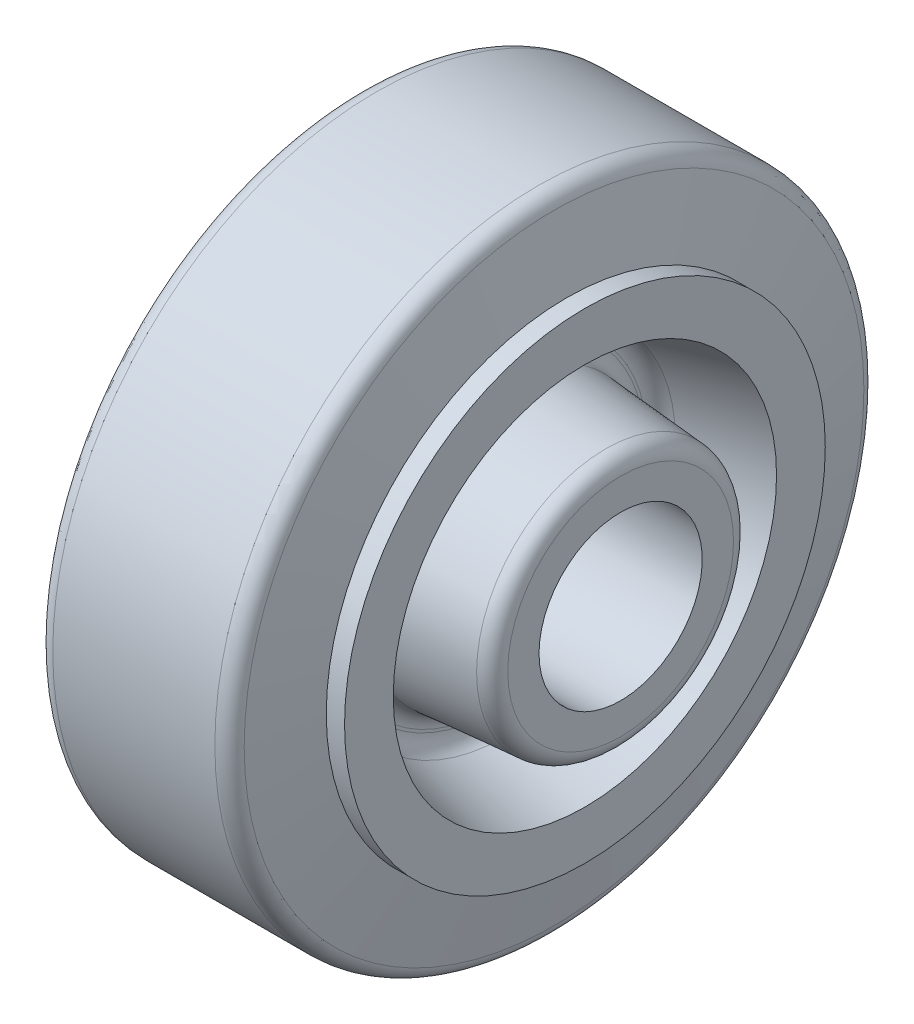
SolidWorks part; units mm, degrees
ref_plane "Front Plane" through (0, 0, 0) normal (0, 0, 1) x (1, 0, 0)
ref_plane "Top Plane" through (0, 0, 0) normal (0, 1, 0) x (1, 0, 0)
ref_plane "Right Plane" through (0, 0, 0) normal (1, 0, 0) x (0, 0, -1)
sketch "Sketch1" plane through (0, 0, 0) normal (0, 0, 1) x (1, 0, 0)
  line L0 (-11.65, -39.8) -> (11.65, -39.8)
  line L1 (-11.65, -39.8) -> (-13.5, -29.6)
  line L2 (15.75, -23.6) -> (4.25, -20.75)
  line L3 (4.25, -20.75) -> (4.25, -17)
  line L4 (4.25, -17) -> (20.15, -15.75)
  line L5 (20.15, -15.75) -> (20.15, -10.05)
  line L6 (0, -39.8) -> (0, 0) construction
  line L7 (0, 0) -> (22.2, 0) construction
  line L8 (20.15, -10.05) -> (-20.15, -10.05)
  line L9 (-20.15, -15.75) -> (-20.15, -10.05)
  line L10 (-4.25, -17) -> (-20.15, -15.75)
  line L11 (-4.25, -20.75) -> (-4.25, -17)
  line L12 (-15.75, -23.6) -> (-4.25, -20.75)
  line L13 (-13.5, -29.6) -> (-15.75, -29.6)
  line L14 (-15.75, -29.6) -> (-15.75, -23.6)
  line L15 (11.65, -39.8) -> (13.5, -29.6)
  line L16 (13.5, -29.6) -> (15.75, -29.6)
  line L17 (15.75, -29.6) -> (15.75, -23.6)
  point P12 (0, -10.05)
  dimension "D1" = 40.3
  dimension "D2" = 31.5
  dimension "D3" = 20.1
  dimension "D4" = 31.5
  dimension "D5" = 79.6
  dimension "D6" = 6
  dimension "D7" = 15.9
  dimension "D8" = 23.3
  dimension "D9" = 27
  dimension "D10" = 47.2
  dimension "D11" = 41.5
  dimension "D12" = 34
revolve "Revolve1" add sketch "Sketch1" angle 360 about L7
fillet "Fillet1" radius 2 8 edges at (4.25, 0, 20.75) (4.25, 0, 17) (-4.25, 0, 17) (-4.25, 0, 20.75) (20.15, 0, 15.75) (-20.15, 0, 15.75) (-11.65, 0, 39.8) (11.65, 0, 39.8)
move or copy body "Body-Move/Copy1" [suppressed] bodies to move or copy 101
